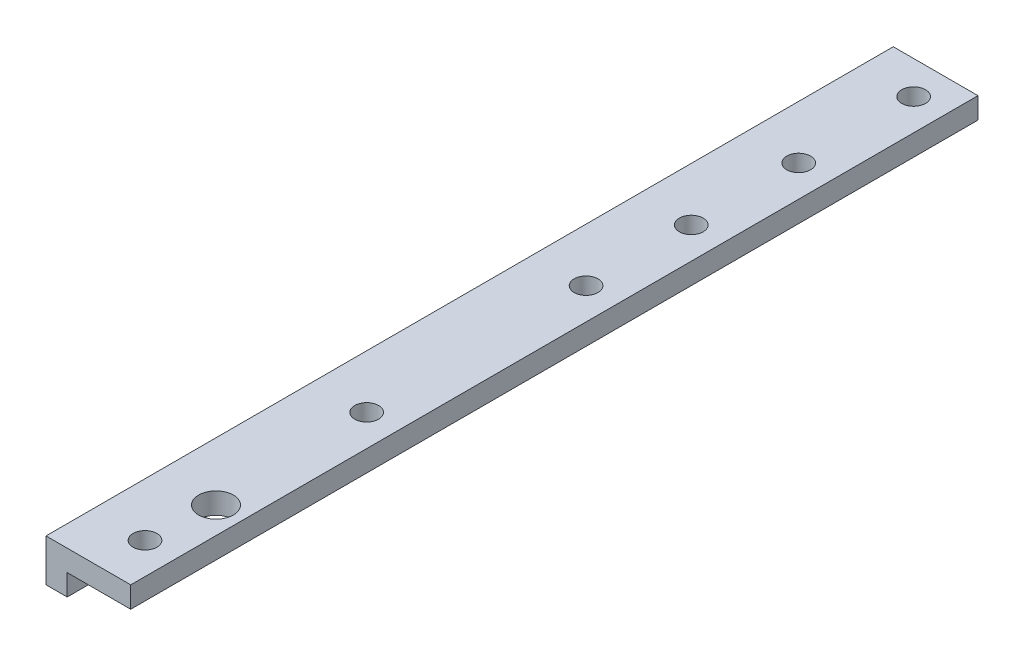
SolidWorks part; units mm, degrees
material "Plain Carbon Steel"
ref_plane "Front Plane" through (0, 0, 0) normal (0, 0, 1) x (1, 0, 0)
ref_plane "Top Plane" through (0, 0, 0) normal (0, 1, 0) x (1, 0, 0)
ref_plane "Right Plane" through (0, 0, 0) normal (1, 0, 0) x (0, 0, -1)
sketch "Sketch1" plane through (0, 0, 0) normal (0, 0, 1) x (1, 0, 0)
  line L0 (0, 0) -> (0, -10)
  line L5 (0, -10) -> (4, -10)
  line L6 (4, -10) -> (4, -4)
  line L11 (4, -4) -> (16, -4)
  line L12 (16, -4) -> (16, 0)
  line L13 (16, 0) -> (0, 0)
  point P0 (0, 0)
  dimension "D1" = 16
  dimension "D2" = 10
  dimension "D3" = 4
  dimension "D4" = 4
extrude "Boss-Extrude1" add sketch "Sketch1" along normal blind 160
sketch "Sketch2" plane through (4, 0, 0) normal (1, 0, 0) x (0, 0, -1)
  line L0 (-120.4489, -8) -> (-160, -8)
  line L2 (-120.4489, -10) -> (-160, -10)
  line L4 (-160, -10) -> (-160, -8)
  line L6 (-120.4489, -10) -> (-120.4489, -8)
  point P3 (-140.2245, -8)
extrude "Cut-Extrude1" cut sketch "Sketch2" against normal up to surface (4 mm away) up to face at (0, -5, 80)
hole_wizard "M4 Clearance Hole1" positions "Sketch3" profile "Sketch4" hole size "M4" standard "ISO" end condition through all
sketch "Sketch3" plane through (0, -4, 0) normal (0, -1, 0) x (-1, 0, 0)
  point P0 (-10.0724, -6.2281)
  point P2 (-10.0724, -27.9379)
  point P4 (-10.0724, -48.2215)
  point P6 (-10.0724, -68.0876)
  point P8 (-10.0724, -109.5175)
  point P10 (-10.0724, -151.3766)
sketch "Sketch4" plane through (10.0724, -4, 6.2281) normal (1, 0, 0) x (0, 0, -1)
  line L0 (0, 0) -> (0, 4)
  line L1 (0, 4) -> (2.25, 4)
  line L2 (2.25, 4) -> (2.25, 0)
  line L5 (2.25, 0) -> (0, 0)
  line L11 (0, -6.35) -> (0, 107.95) construction
  dimension "Thru Hole Dia." = 4.5
  dimension "Thru Hole Depth" = 4
sketch "Sketch5" plane through (0, -4, 0) normal (0, -1, 0) x (1, 0, 0)
  circle A0 centre (11, 138.8979) radius 3.275
extrude "Cut-Extrude2" cut sketch "Sketch5" against normal blind 10
